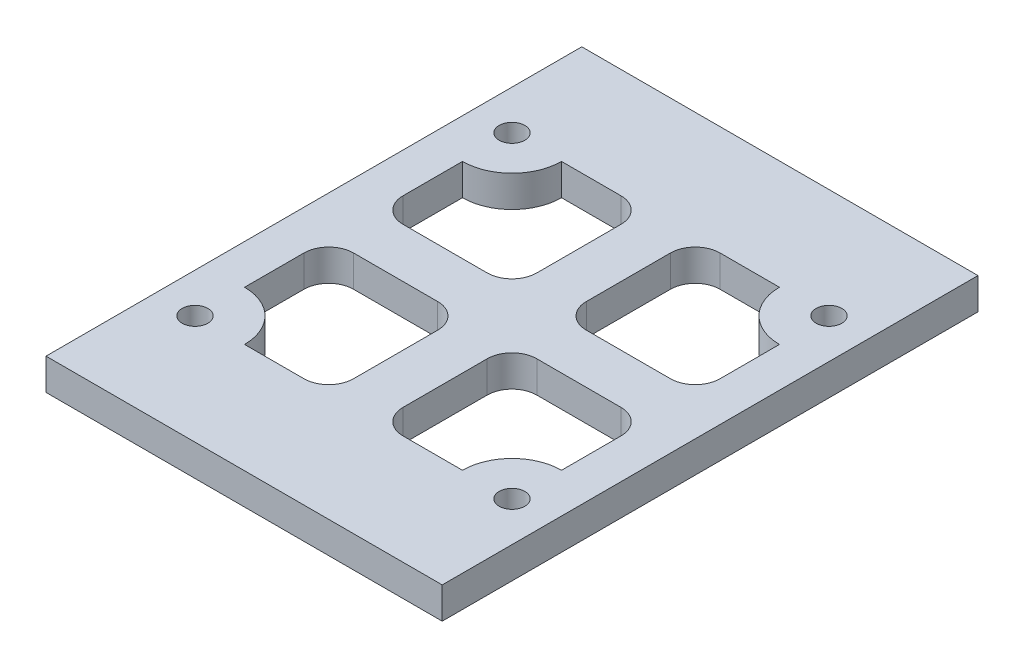
SolidWorks part; units mm, degrees
ref_plane "Alzado" through (0, 0, 0) normal (0, 0, 1) x (1, 0, 0)
ref_plane "Planta" through (0, 0, 0) normal (0, 1, 0) x (1, 0, 0)
ref_plane "Vista lateral" through (0, 0, 0) normal (1, 0, 0) x (0, 0, -1)
sketch "Sketch1" plane through (0, 0, 0) normal (0, 1, 0) x (1, 0, 0)
  line L1 (-40, -54.09) -> (40, -54.09)
  line L2 (-40, -54.09) -> (-40, 54.09)
  line L3 (-40, 54.09) -> (40, 54.09)
  line L4 (40, -54.09) -> (40, 54.09)
  line L5 (-40, -54.09) -> (40, 54.09) construction
  line L6 (-40, 54.09) -> (40, -54.09) construction
  line L7 (-32, -32) -> (32, -32) construction
  line L8 (-32, -32) -> (-32, 32) construction
  line L9 (-32, 32) -> (32, 32) construction
  line L10 (32, -32) -> (32, 32) construction
  line L11 (-32, -32) -> (32, 32) construction
  line L12 (-32, 32) -> (32, -32) construction
  circle A0 centre (-32, 32) radius 2.6
  circle A1 centre (32, 32) radius 2.6
  circle A2 centre (32, -32) radius 2.6
  circle A3 centre (-32, -32) radius 2.6
  point P0 (0, 0)
  point P5 (0, 0)
  point P11 (0, 0)
  point P13 (0, 0)
  point P14 (0, 0)
  point P21 (0, 0)
  dimension "D4" = 5.2
  dimension "D1" = 108.18
  dimension "D2" = 80
  dimension "D3" = 64
  dimension "D5" = 4
extrude "Boss-Extrude1" add sketch "Sketch1" along normal blind 6.35
sketch "Sketch2" plane through (0, 6.35, 0) normal (0, 1, 0) x (1, 0, 0)
  line L0 (0, 54.09) -> (0, -54.09) construction
  line L1 (40, 54.09) -> (-40, 54.09) construction
  line L2 (-40, -54.09) -> (40, -54.09) construction
  line L3 (40, 0) -> (-40, 0) construction
  line L4 (40, -54.09) -> (40, 54.09) construction
  line L5 (-40, 54.09) -> (-40, -54.09) construction
  line L6 (-27, -5) -> (-10, -5)
  line L7 (-5, -10) -> (-5, -27)
  line L8 (-10, -32) -> (-22, -32)
  line L9 (-32, -22) -> (-32, -10)
  line L10 (-22, 32) -> (-10, 32)
  line L11 (-5, 27) -> (-5, 10)
  line L12 (-10, 5) -> (-27, 5)
  line L13 (-32, 10) -> (-32, 22)
  line L14 (32, 22) -> (32, 10)
  line L15 (27, 5) -> (10, 5)
  line L16 (5, 10) -> (5, 27)
  line L17 (10, 32) -> (22, 32)
  line L18 (22, -32) -> (10, -32)
  line L19 (5, -27) -> (5, -10)
  line L20 (10, -5) -> (27, -5)
  line L21 (32, -10) -> (32, -22)
  arc A0 (-22, -32) -> (-32, -22) centre (-32, -32) ccw
  circle A1 centre (-32, -32) radius 2.6 construction
  arc A2 (-5, -27) -> (-10, -32) centre (-10, -27) cw
  arc A3 (-10, -5) -> (-5, -10) centre (-10, -10) cw
  arc A4 (-27, -5) -> (-32, -10) centre (-27, -10) ccw
  arc A5 (-5, 27) -> (-10, 32) centre (-10, 27) ccw
  arc A6 (-5, 10) -> (-10, 5) centre (-10, 10) cw
  arc A7 (-27, 5) -> (-32, 10) centre (-27, 10) cw
  arc A8 (-32, 22) -> (-22, 32) centre (-32, 32) ccw
  arc A9 (27, 5) -> (32, 10) centre (27, 10) ccw
  arc A10 (10, 5) -> (5, 10) centre (10, 10) cw
  arc A11 (5, 27) -> (10, 32) centre (10, 27) cw
  arc A12 (22, 32) -> (32, 22) centre (32, 32) ccw
  arc A13 (5, -27) -> (10, -32) centre (10, -27) ccw
  arc A14 (5, -10) -> (10, -5) centre (10, -10) cw
  arc A15 (27, -5) -> (32, -10) centre (27, -10) cw
  arc A16 (32, -22) -> (22, -32) centre (32, -32) ccw
  point P20 (0, 0)
  point P65 (0, 0)
  dimension "D1" = 5
  dimension "D3" = 10
  dimension "D4" = 5
  dimension "D2" = 5
  dimension "D5" = 4
extrude "Cut-Extrude1" cut sketch "Sketch2" against normal blind 6.35
